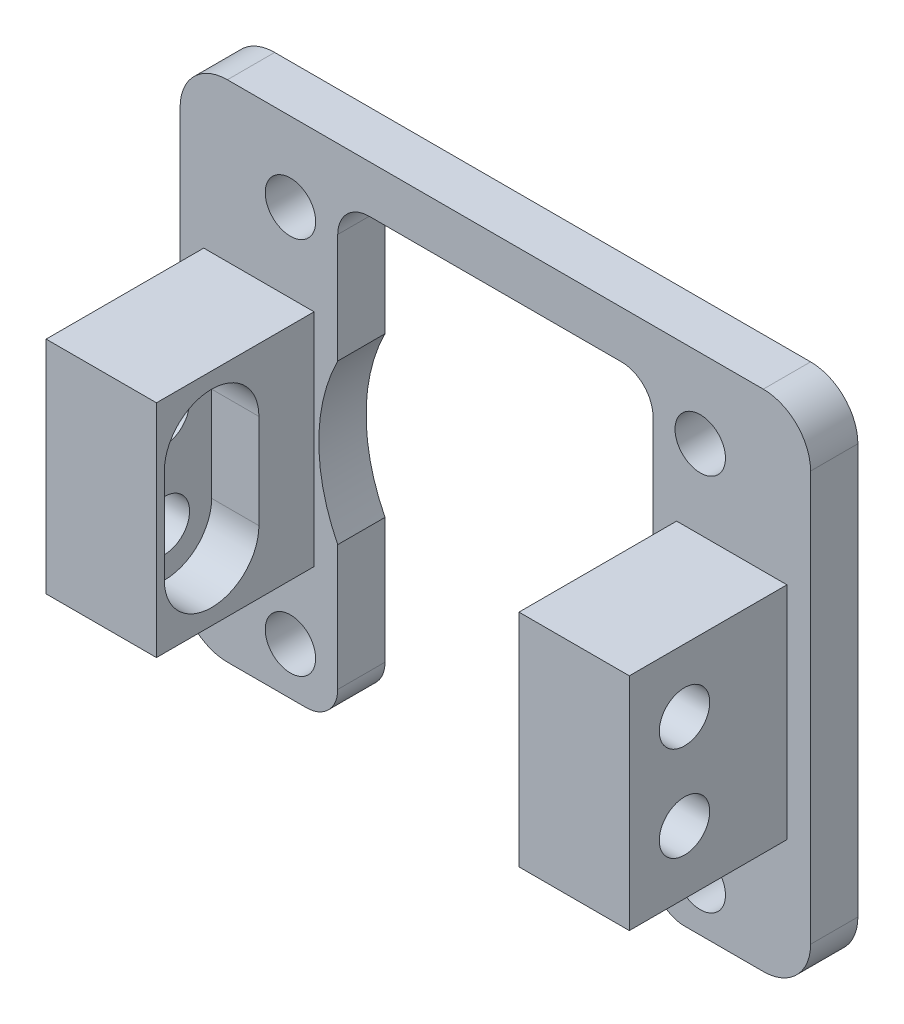
SolidWorks part; units mm, degrees
material "ABS"
ref_plane "前视基准面" through (0, 0, 0) normal (0, 0, 1) x (1, 0, 0)
ref_plane "上视基准面" through (0, 0, 0) normal (0, 1, 0) x (1, 0, 0)
ref_plane "右视基准面" through (0, 0, 0) normal (1, 0, 0) x (0, 0, -1)
sketch "草图1" plane through (0, 0, 0) normal (0, 0, 1) x (1, 0, 0)
  line L1 (-15, 105) -> (15, 105) construction
  line L2 (-10, 103.9981) -> (-10, 95.0438)
  line L3 (15, 75) -> (-15, 75) construction
  line L4 (0, 105) -> (0, 75) construction
  line L5 (10, 84.9562) -> (10, 75)
  line L8 (-20, 104) -> (-20, 78)
  line L12 (-10, 75) -> (-17, 75)
  line L13 (-10, 84.9562) -> (-10, 75)
  line L14 (10, 75) -> (17, 75)
  line L15 (20, 104) -> (20, 78)
  line L17 (10, 103.9981) -> (10, 95.0438)
  line L19 (-10, 103.9981) -> (10, 103.9981)
  line L20 (-17, 107) -> (17, 107)
  arc A0 (-10, 95.0438) -> (-10, 84.9562) centre (0, 90) ccw
  circle A1 centre (-13, 102) radius 1.6
  circle A2 centre (-13, 78) radius 1.6
  arc A3 (10, 95.0438) -> (10, 84.9562) centre (0, 90) cw
  arc A8 (-17, 107) -> (-20, 104) centre (-17, 104) ccw
  arc A9 (-20, 78) -> (-17, 75) centre (-17, 78) ccw
  circle A10 centre (13, 102) radius 1.6
  circle A11 centre (13, 78) radius 1.6
  arc A12 (20, 78) -> (17, 75) centre (17, 78) cw
  arc A13 (17, 107) -> (20, 104) centre (17, 104) cw
  dimension "D2" = 7
  dimension "D4" = 26
  dimension "D5" = 3
  dimension "D6" = 3
  dimension "D1" = 7
extrude "凸台-拉伸1" add sketch "草图1" along normal blind 3
sketch "草图2" plane through (0, 0, 3) normal (0, 0, 1) x (1, 0, 0)
  line L0 (17, 107) -> (-17, 107) construction
  line L1 (-18.5, 97) -> (-11.5, 97)
  line L3 (-18.5, 83) -> (-11.5, 83)
  line L4 (-11.5, 97) -> (-11.5, 83)
  line L5 (18.5, 83) -> (11.5, 83)
  line L6 (-17, 75) -> (-10, 75) construction
  line L7 (-18.5, 97) -> (-18.5, 83)
  line L8 (-18.5, 4.5) -> (-18.5, 100.216) construction
  line L9 (0, 107) -> (0, 74.6809) construction
  line L10 (18.5, 97) -> (18.5, 83)
  line L11 (11.5, 97) -> (11.5, 83)
  line L12 (18.5, 97) -> (11.5, 97)
  dimension "D1" = 10
  dimension "D2" = 8
  dimension "D3" = 7
extrude "凸台-拉伸2" add sketch "草图2" along normal blind 10
sketch "草图4" plane through (-18.5, 0, 0) normal (-1, 0, 0) x (0, 0, 1)
  line L0 (9.5, 97) -> (9.5, 83) construction
  line L1 (13, 97) -> (3, 97) construction
  line L2 (13, 83) -> (3, 83) construction
  line L3 (13, 97) -> (13, 83) construction
  circle A0 centre (9.5, 93) radius 1.6
  circle A1 centre (9.5, 87) radius 1.6
  dimension "D1" = 4
  dimension "D2" = 4
  dimension "D3" = 3.5
extrude "切除-拉伸1" cut sketch "草图4" against normal through all both and the other way through all
fillet "圆角1" radius 2 4 edges at (-10, 75, 1.5) (10, 75, 1.5) (10, 103.9981, 1.5) (-10, 103.9981, 1.5)
sketch "草图5" plane through (11.5, 0, 0) normal (-1, 0, 0) x (0, 0, 1)
  line L0 (9.5, 93) -> (9.5, 87) construction
  line L1 (12.5, 93) -> (12.5, 87)
  line L2 (6.5, 93) -> (6.5, 87)
  arc A0 (12.5, 93) -> (6.5, 93) centre (9.5, 93) ccw
  arc A1 (6.5, 87) -> (12.5, 87) centre (9.5, 87) ccw
  point P4 (9.5, 90)
extrude "切除-拉伸2" cut sketch "草图5" against normal blind 3
sketch "草图6" plane through (-11.5, 0, 0) normal (1, 0, 0) x (0, 0, -1)
  line L0 (-9.5, 93) -> (-9.5, 87) construction
  line L1 (-6.5, 93) -> (-6.5, 87)
  line L2 (-12.5, 93) -> (-12.5, 87)
  arc A0 (-6.5, 93) -> (-12.5, 93) centre (-9.5, 93) ccw
  arc A1 (-12.5, 87) -> (-6.5, 87) centre (-9.5, 87) ccw
  point P4 (-9.5, 90)
extrude "切除-拉伸3" cut sketch "草图6" against normal blind 3
